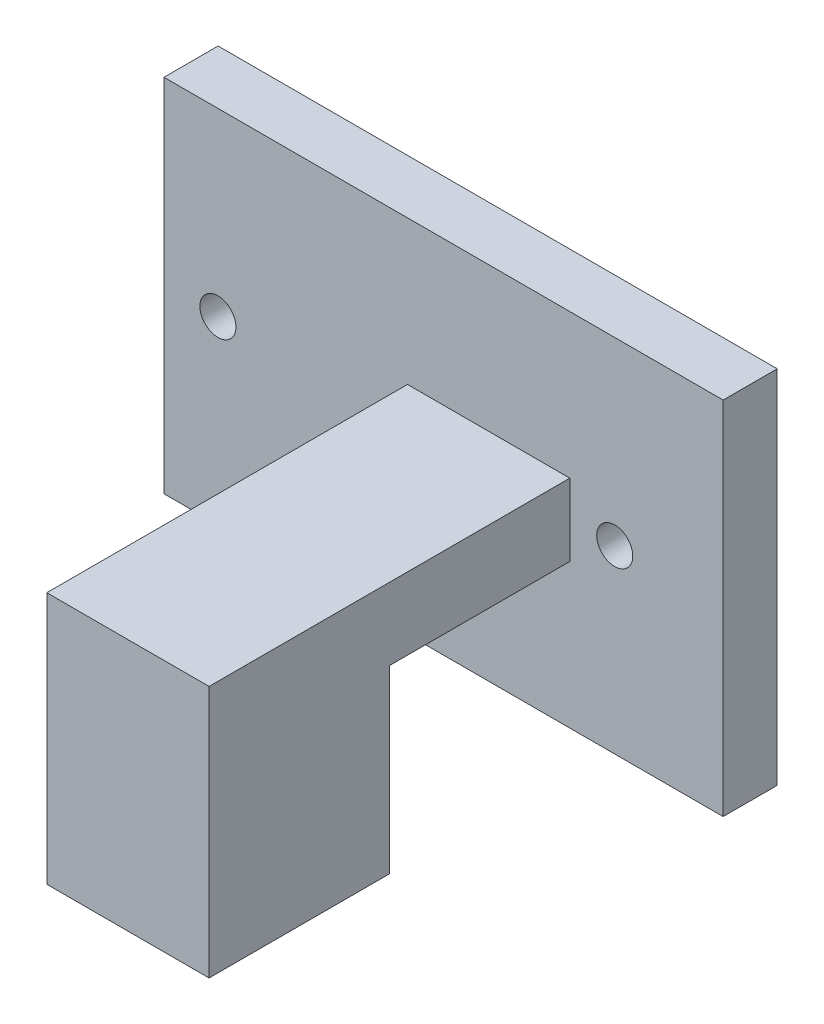
SolidWorks part; units mm, degrees
ref_plane "Plan de face" through (0, 0, 0) normal (0, 0, 1) x (1, 0, 0)
ref_plane "Plan de dessus" through (0, 0, 0) normal (0, 1, 0) x (1, 0, 0)
ref_plane "Plan de droite" through (0, 0, 0) normal (1, 0, 0) x (0, 0, -1)
sketch "Esquisse1" plane through (0, 0, 0) normal (0, 0, 1) x (1, 0, 0)
  line L1 (-23.765, 7.394) -> (2.235, 7.394)
  line L2 (-23.765, 7.394) -> (-23.765, -12.606)
  line L3 (-23.765, -12.606) -> (2.235, -12.606)
  line L4 (2.235, 7.394) -> (2.235, -12.606)
  line L5 (-23.765, 7.394) -> (2.235, -12.606) construction
  line L6 (-23.765, -12.606) -> (2.235, 7.394) construction
  point P0 (-10.765, -2.606)
  dimension "D1" = 26
  dimension "D2" = 20
extrude "Boss.-Extru.1" add sketch "Esquisse1" along normal blind 3
sketch "Esquisse2" plane through (0, 0, 3) normal (0, 0, 1) x (1, 0, 0)
  line L0 (-23.765, -2.606) -> (2.235, -2.606) construction
  line L1 (-23.765, 7.394) -> (-23.765, -12.606) construction
  line L2 (2.235, -12.606) -> (2.235, 7.394) construction
  line L3 (-10.765, 7.394) -> (-10.765, -12.606) construction
  line L4 (2.235, 7.394) -> (-23.765, 7.394) construction
  line L5 (-23.765, -12.606) -> (2.235, -12.606) construction
  circle A0 centre (-20.775, -2.606) radius 1
  circle A1 centre (1.225, -2.606) radius 1
  dimension "D1" = 2.99
  dimension "D2" = 22
extrude "Enlèv. mat.-Extru.1" cut sketch "Esquisse2" against normal blind 10
sketch "Esquisse3" plane through (0, 0, 3) normal (0, 0, 1) x (1, 0, 0)
  line L0 (-23.765, -2.606) -> (2.235, -2.606) construction
  line L1 (-23.765, 7.394) -> (-23.765, -12.606) construction
  line L2 (2.235, -12.606) -> (2.235, 7.394) construction
  line L3 (-10.765, 7.394) -> (-10.765, -12.606) construction
  line L4 (2.235, 7.394) -> (-23.765, 7.394) construction
  line L5 (-23.765, -12.606) -> (2.235, -12.606) construction
  line L7 (-1.265, -4.606) -> (-10.265, -4.606)
  line L8 (-1.265, -4.606) -> (-1.265, -0.606)
  line L9 (-1.265, -0.606) -> (-10.265, -0.606)
  line L10 (-10.265, -4.606) -> (-10.265, -0.606)
  line L11 (-1.265, -4.606) -> (-10.265, -0.606) construction
  line L12 (-1.265, -0.606) -> (-10.265, -4.606) construction
  point P12 (-10.765, -2.606)
  dimension "D1" = 9
  dimension "D2" = 4
  dimension "D3" = 13.5
extrude "Boss.-Extru.2" add sketch "Esquisse3" along normal blind 20
sketch "Esquisse10" plane through (0, -4.606, 0) normal (0, -1, 0) x (-1, 0, 0)
  line L0 (10.265, -23) -> (10.265, -3) construction
  line L1 (1.265, -23) -> (10.265, -23)
  line L2 (1.265, -23) -> (1.265, -13)
  line L3 (1.265, -13) -> (10.265, -13)
  line L4 (10.265, -23) -> (10.265, -13)
  dimension "D1" = 10
extrude "Boss.-Extru.3" add sketch "Esquisse10" along normal blind 10
sketch "Esquisse12" plane through (0, -14.606, 0) normal (0, -1, 0) x (1, 0, 0)
  line L0 (-1.265, 13) -> (-1.265, 23) construction
  line L1 (-1.265, 23) -> (-10.265, 23) construction
  line L8 (-1.765, 18) -> (-2.8624, 18.758)
  line L9 (-1.765, 18) -> (-2.8627, 17.2406)
  line L10 (-2.3009, 16) -> (-3.6312, 15.8912)
  line L11 (-2.3009, 16) -> (-2.8723, 17.2051)
  line L12 (-3.765, 14.5359) -> (-4.9715, 15.1069)
  line L13 (-3.765, 14.5359) -> (-3.6573, 15.8652)
  line L14 (-5.765, 14) -> (-6.5244, 15.0977)
  line L15 (-5.765, 14) -> (-5.0071, 15.0973)
  line L16 (-7.765, 14.5359) -> (-7.8738, 15.8662)
  line L17 (-7.765, 14.5359) -> (-6.56, 15.1072)
  line L18 (-9.2291, 16) -> (-8.6582, 17.2065)
  line L19 (-9.2291, 16) -> (-7.8999, 15.8923)
  line L20 (-9.765, 18) -> (-8.6673, 18.7594)
  line L21 (-9.765, 18) -> (-8.6677, 17.242)
  line L22 (-9.2291, 20) -> (-7.8988, 20.1088)
  line L23 (-9.2291, 20) -> (-8.6578, 18.7949)
  line L24 (-7.765, 21.4641) -> (-6.5586, 20.8931)
  line L25 (-7.765, 21.4641) -> (-7.8728, 20.1348)
  line L26 (-5.765, 22) -> (-5.0057, 20.9023)
  line L27 (-5.765, 22) -> (-6.523, 20.9027)
  line L28 (-3.765, 21.4641) -> (-3.6563, 20.1338)
  line L29 (-3.765, 21.4641) -> (-4.9701, 20.8928)
  line L30 (-2.3009, 20) -> (-2.8719, 18.7935)
  line L31 (-2.3009, 20) -> (-3.6302, 20.1077)
  arc A1 (-3.6302, 20.1077) -> (-3.6563, 20.1338) centre (-5.765, 18) ccw
  arc A2 (-2.8624, 18.758) -> (-2.8719, 18.7935) centre (-5.765, 18) ccw
  arc A3 (-2.8723, 17.2051) -> (-2.8627, 17.2406) centre (-5.765, 18) ccw
  arc A4 (-3.6573, 15.8652) -> (-3.6312, 15.8912) centre (-5.765, 18) ccw
  arc A5 (-5.0071, 15.0973) -> (-4.9715, 15.1069) centre (-5.765, 18) ccw
  arc A6 (-6.56, 15.1072) -> (-6.5244, 15.0977) centre (-5.765, 18) ccw
  arc A7 (-7.8999, 15.8923) -> (-7.8738, 15.8662) centre (-5.765, 18) ccw
  arc A8 (-8.6677, 17.242) -> (-8.6582, 17.2065) centre (-5.765, 18) ccw
  arc A9 (-8.6578, 18.7949) -> (-8.6673, 18.7594) centre (-5.765, 18) ccw
  arc A10 (-7.8728, 20.1348) -> (-7.8988, 20.1088) centre (-5.765, 18) ccw
  arc A11 (-6.523, 20.9027) -> (-6.5586, 20.8931) centre (-5.765, 18) ccw
  arc A12 (-4.9701, 20.8928) -> (-5.0057, 20.9023) centre (-5.765, 18) ccw
  point P54 (-5.765, 18)
  dimension "D1" = 1.3336
  dimension "D2" = 1.3347
  dimension "D4" = 0.5
  dimension "D5" = 1
  dimension "D3" = 12
extrude "Enlèv. mat.-Extru.9" cut sketch "Esquisse12" against normal blind 5
sketch "Esquisse13" plane through (2.235, 0, 0) normal (1, 0, 0) x (0, 0, -1)
  line L1 (-3, -12.606) -> (0, -12.606)
  line L2 (-3, -12.606) -> (-3, 7.394)
  line L3 (-3, 7.394) -> (0, 7.394)
  line L4 (0, -12.606) -> (0, 7.394)
extrude "Boss.-Extru.4" add sketch "Esquisse13" along normal blind 5
